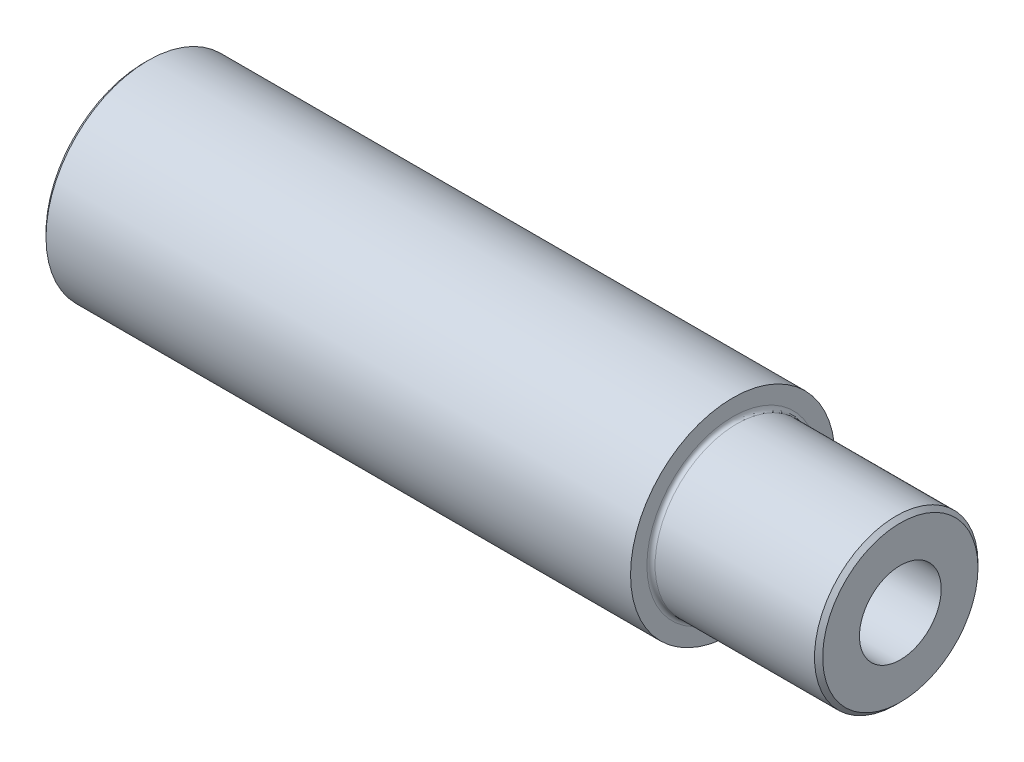
SolidWorks part; units mm, degrees
material "2014 Alloy"
ref_plane "Front Plane" through (0, 0, 0) normal (0, 0, 1) x (1, 0, 0)
ref_plane "Top Plane" through (0, 0, 0) normal (0, 1, 0) x (1, 0, 0)
ref_plane "Right Plane" through (0, 0, 0) normal (1, 0, 0) x (0, 0, -1)
sketch "Sketch1" plane through (0, 0, 0) normal (1, 0, 0) x (0, 0, -1)
  circle A0 centre (0, 0) radius 12.5
  circle A1 centre (0, 0) radius 5
  dimension "D1" = 25
  dimension "D2" = 10
extrude "Boss-Extrude1" add sketch "Sketch1" along normal blind 92.5
sketch "Sketch2" plane through (92.5, 0, 0) normal (1, 0, 0) x (0, 0, -1)
  circle A0 centre (0, 0) radius 10
  dimension "D1" = 20
extrude "Cut-Extrude1" cut sketch "Sketch2" against normal blind 20.5 flip side to cut
fillet "Fillet1" radius 0.5 1 edges at (72, 0, -10)
chamfer "Chamfer1" distance 0.5 angle 45 2 edges at (92.5, 0, -10) (0, 0, -12.5)
